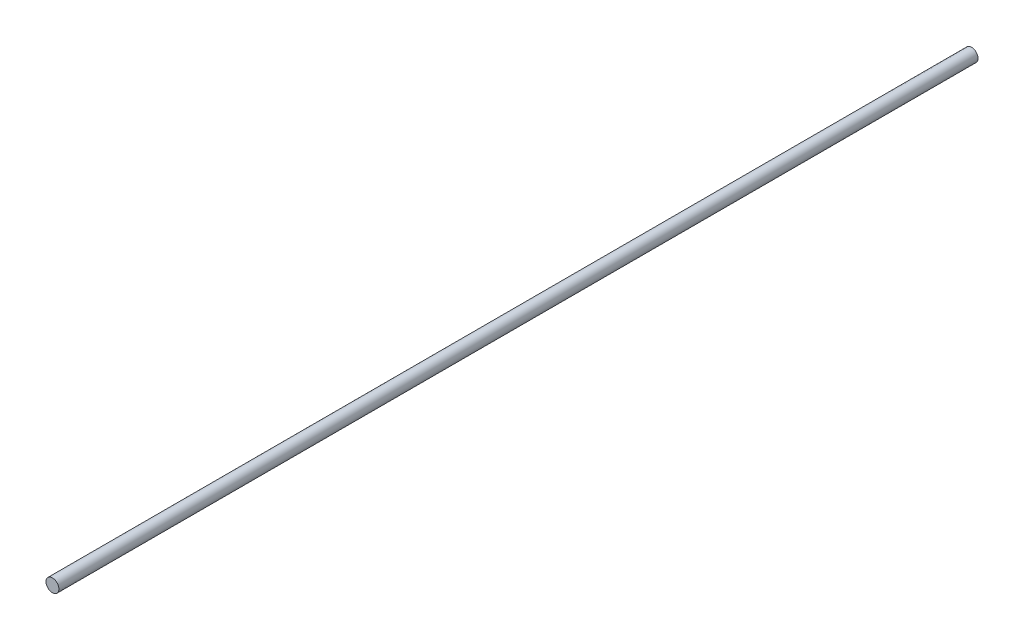
SolidWorks part; units mm, degrees
ref_plane "Front Plane" through (0, 0, 0) normal (0, 0, 1) x (1, 0, 0)
ref_plane "Top Plane" through (0, 0, 0) normal (0, 1, 0) x (1, 0, 0)
ref_plane "Right Plane" through (0, 0, 0) normal (1, 0, 0) x (0, 0, -1)
sketch "Sketch1" plane through (0, 0, 0) normal (0, 0, 1) x (1, 0, 0)
  circle A0 centre (0, 0) radius 4
  dimension "D1" = 8
extrude "Boss-Extrude1" add sketch "Sketch1" along normal mid plane 570
